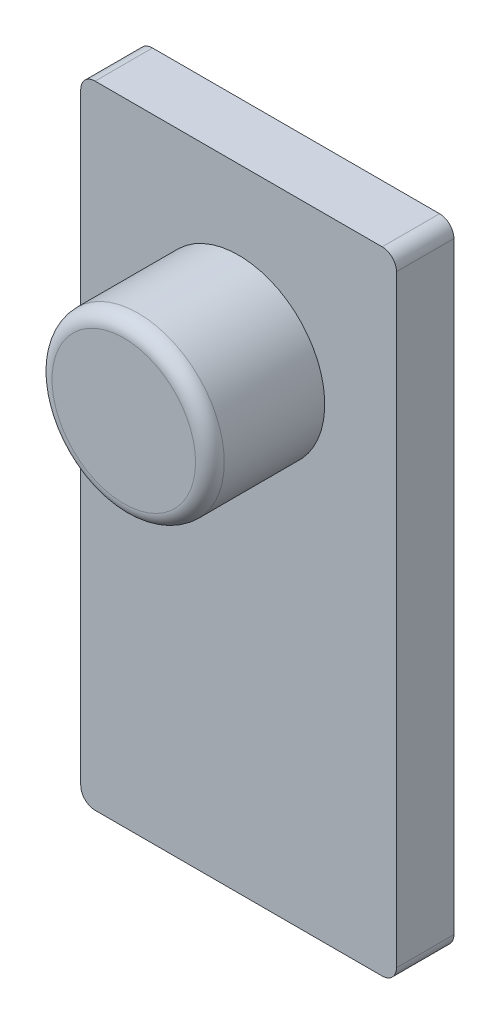
SolidWorks part; units mm, degrees
ref_plane "Front Plane" through (0, 0, 0) normal (0, 0, 1) x (1, 0, 0)
ref_plane "Top Plane" through (0, 0, 0) normal (0, 1, 0) x (1, 0, 0)
ref_plane "Right Plane" through (0, 0, 0) normal (1, 0, 0) x (0, 0, -1)
sketch "Sketch1" plane through (0, 0, 0) normal (0, 0, 1) x (1, 0, 0)
  line L1 (-11.5, -11) -> (-0.5, -11)
  line L2 (-11.5, -11) -> (-11.5, 11)
  line L3 (-11.5, 11) -> (-0.5, 11)
  line L4 (-0.5, -11) -> (-0.5, 11)
extrude "Boss-Extrude1" add sketch "Sketch1" along normal blind 2
sketch "Sketch2" plane through (0, 0, 2) normal (0, 0, 1) x (1, 0, 0)
  circle A0 centre (-6, 5.25) radius 3
  dimension "D1" = 6
extrude "Boss-Extrude2" add sketch "Sketch2" along normal blind 4
fillet "Fillet1" radius 0.5 5 edges at (-3, 5.25, 6) (-0.5, -11, 1) (-11.5, -11, 1) (-0.5, 11, 1) (-11.5, 11, 1)
